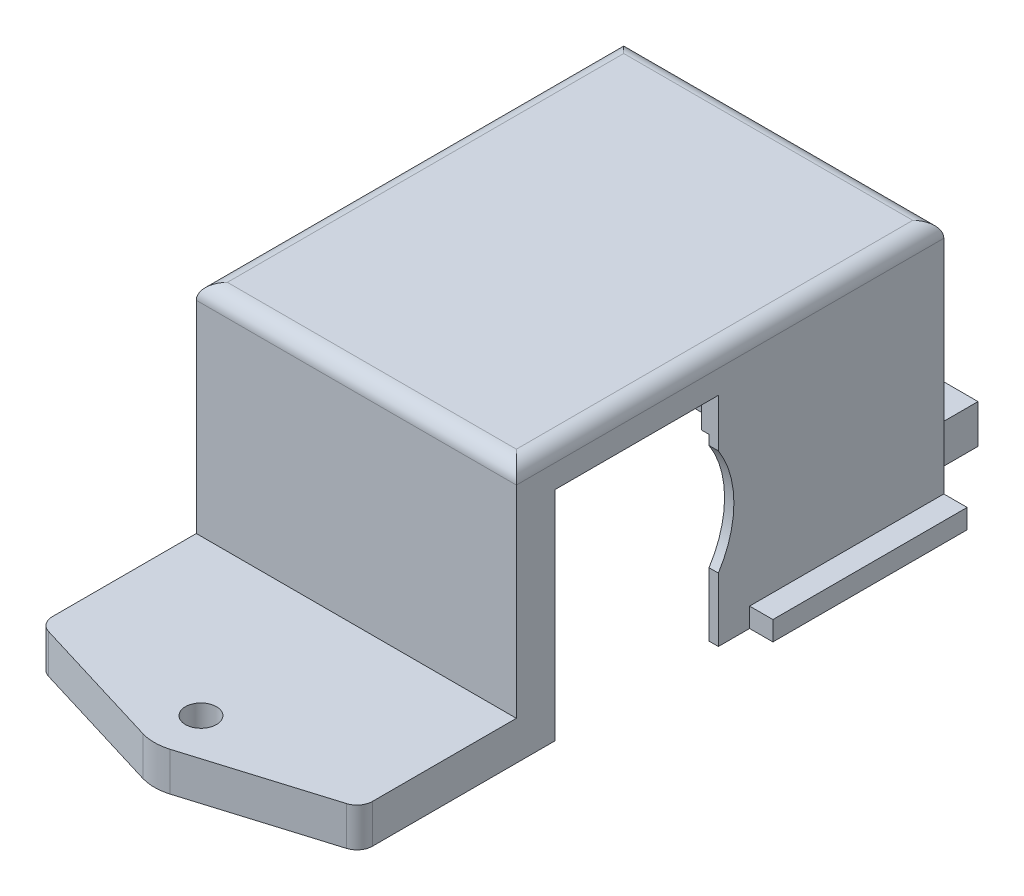
SolidWorks part; units mm, degrees
ref_plane "Front Plane" through (0, 0, 0) normal (0, 0, 1) x (1, 0, 0)
ref_plane "Top Plane" through (0, 0, 0) normal (0, 1, 0) x (1, 0, 0)
ref_plane "Right Plane" through (0, 0, 0) normal (1, 0, 0) x (0, 0, -1)
sketch "Sketch1" plane through (0, 0, 0) normal (0, 1, 0) x (1, 0, 0)
  line L1 (-19.891, 13.2956) -> (19.109, 13.2956)
  line L2 (-19.891, 13.2956) -> (-19.891, -35.9244)
  line L3 (-19.891, -35.9244) -> (19.109, -35.9244)
  line L4 (19.109, 13.2956) -> (19.109, -35.9244)
extrude "Boss-Extrude2" add sketch "Sketch1" along normal blind 30
sketch "Sketch3" plane through (0, 0, 35.9244) normal (0, 0, 1) x (1, 0, 0)
  line L0 (-19.891, 28) -> (19.109, 28)
  line L1 (-19.891, 30) -> (-19.891, 0) construction
  line L2 (19.109, 30) -> (19.109, 0) construction
  line L3 (17.109, 30) -> (17.109, 0) construction
  line L4 (-19.891, 30) -> (19.109, 30) construction
  line L5 (-19.891, 0) -> (19.109, 0) construction
  line L6 (-16.141, 30) -> (-16.141, 0)
  line L7 (-17.891, 30) -> (-17.891, 0)
  line L8 (16.109, 28) -> (16.109, -0.33)
  line L9 (-17.891, 28) -> (17.109, 28)
  line L10 (-17.891, 28) -> (-17.891, 0)
  line L11 (-17.891, 0) -> (17.109, 0)
  line L12 (17.109, 28) -> (17.109, 0)
  line L13 (-17.891, 25.5) -> (-16.141, 25.5)
  line L14 (-17.891, 25.5) -> (-17.891, 5.5)
  line L15 (-17.891, 5.5) -> (-16.141, 5.5)
  line L16 (-16.141, 25.5) -> (-16.141, 5.5)
  line L18 (16.109, 23.05) -> (17.109, 23.05)
  line L19 (16.109, 23.05) -> (16.109, 7.95)
  line L20 (16.109, 7.95) -> (17.109, 7.95)
  line L21 (17.109, 23.05) -> (17.109, 7.95)
  point P22 (-17.016, 5.5)
  point P29 (16.609, 23.05)
  point P30 (16.609, 7.95)
  line M13 (-19.891, 0) -> (19.109, 0)
  dimension "D1" = 3.75
  dimension "D2" = 2
  dimension "D3" = 1.75
  dimension "D4" = 2
  dimension "D5" = 2.5
  dimension "D6" = 5.5
  dimension "D7" = 33.25
  dimension "D8" = 1
  dimension "D9" = 4.95
  dimension "D10" = 7.95
extrude "Cut-Extrude3" cut sketch "Sketch3" against normal blind 47.22 contours L8 L0 L6 M13 | L10 L15 L6 L13 | L8 L20 L12 L18
sketch "Sketch7" plane through (-19.891, 0, 0) normal (-1, 0, 0) x (0, 0, 1)
  line L0 (8.7044, 30) -> (8.7044, 0)
  line L1 (-13.2956, 30) -> (35.9244, 30) construction
  line L2 (-13.2956, 0) -> (35.9244, 0) construction
  line L3 (-13.2956, 30) -> (-13.2956, 0) construction
  line L4 (-13.2956, 15) -> (35.9244, 15)
  line L5 (35.9244, 30) -> (35.9244, 0) construction
  circle A0 centre (24.3244, 15) radius 12.6
  dimension "D2" = 11.6
  dimension "D1" = 22
extrude "Cut-Extrude4" cut sketch "Sketch7" against normal blind 47.22 contours L2 A0 L4 | L4 A0 L2
sketch "Sketch8" plane through (-19.891, 0, 0) normal (-1, 0, 0) x (0, 0, 1)
  line L0 (-13.2956, 30) -> (35.9244, 30) construction
  line L1 (8.6339, 30) -> (35.9244, 30)
  line L2 (8.6339, 30) -> (8.6339, 0)
  line L3 (8.6339, 0) -> (35.9244, 0)
  line L4 (35.9244, 30) -> (35.9244, 0)
  line L5 (-13.2956, 0) -> (35.9244, 0) construction
  line L6 (35.9244, 10.0807) -> (35.9244, 0) construction
  line L8 (8.6339, 30) -> (17.6339, 30)
  line L9 (8.6339, 30) -> (8.6339, 27)
  line L10 (8.6339, 27) -> (17.6339, 27)
  line L11 (17.6339, 30) -> (17.6339, 27)
  line L12 (8.6339, 0) -> (17.6339, 0)
  line L13 (8.6339, 0) -> (8.6339, 4)
  line L14 (8.6339, 4) -> (17.6339, 4)
  line L15 (17.6339, 0) -> (17.6339, 4)
  line M1 (35.9244, 0) -> (35.9244, 10.0807)
  arc M2 (35.9244, 10.0807) -> (35.9244, 19.9193) centre (24.3244, 15) cw
  line M3 (35.9244, 19.9193) -> (35.9244, 30)
  line M4 (35.9244, 30) -> (-13.2956, 30)
extrude "Cut-Extrude5" cut sketch "Sketch8" against normal blind 3.75 contours L15 L3 L11 L10 L2 L14 M1 M2 M3 M4
sketch "Sketch9" plane through (19.109, 0, 0) normal (1, 0, 0) x (0, 0, -1)
  line L0 (-35.9244, 0) -> (13.2956, 0) construction
  line L1 (-35.9244, 30) -> (-13.7244, 30)
  line L2 (-35.9244, 30) -> (-35.9244, 0)
  line L3 (-35.9244, 0) -> (-13.7244, 0)
  line L4 (-13.7244, 30) -> (-13.7244, 0)
  dimension "D1" = 22.2
extrude "Cut-Extrude7" cut sketch "Sketch9" against normal through all
sketch "Sketch11" plane through (0, 0, 13.7244) normal (0, 0, 1) x (1, 0, 0)
  line L0 (-18.891, 30) -> (-18.891, 0)
  line L1 (19.109, 0) -> (-19.891, 0)
  line L2 (19.109, 0) -> (19.109, 30)
  line L3 (19.109, 30) -> (-19.891, 30)
  line L4 (-19.891, 0) -> (-19.891, 30)
  line L5 (18.309, 30) -> (18.309, 0)
  line M9 (19.109, 0) -> (19.109, 8.1882)
  line M10 (19.109, 8.1882) -> (17.109, 8.1882)
  dimension "D1" = 1
  dimension "D2" = 0.8
extrude "Cut-Extrude8" cut sketch "Sketch11" against normal through all contours L3 L5 L2 M10 | L5 L1 M10 M9
sketch "Sketch12" plane through (18.309, 0, 0) normal (1, 0, 0) x (0, 0, -1)
  line L1 (13.2956, 0) -> (-9.7044, 0)
  line L2 (13.2956, 0) -> (13.2956, 2.5)
  line L3 (13.2956, 2.5) -> (-9.7044, 2.5)
  line L4 (-9.7044, 0) -> (-9.7044, 2.5)
extrude "Boss-Extrude3" add sketch "Sketch12" along normal blind 3
sketch "Sketch13" plane through (-19.891, 0, 0) normal (-1, 0, 0) x (0, 0, 1)
  line L1 (-13.2956, 0) -> (9.7044, 0)
  line L2 (-13.2956, 0) -> (-13.2956, 2.5)
  line L3 (-13.2956, 2.5) -> (9.7044, 2.5)
  line L4 (9.7044, 0) -> (9.7044, 2.5)
extrude "Boss-Extrude4" add sketch "Sketch13" along normal blind 3
sketch "Sketch14" plane through (-16.141, 0, 0) normal (1, 0, 0) x (0, 0, -1)
  line L0 (-13.7244, 0) -> (-13.7244, 8.1882) construction
  line L1 (-13.7244, 3) -> (13.2956, 3)
  line L2 (-13.7244, 3) -> (-13.7244, 0)
  line L3 (-13.7244, 0) -> (13.2956, 0)
  line L4 (13.2956, 3) -> (13.2956, 0)
extrude "Boss-Extrude5" add sketch "Sketch14" along normal up to next
sketch "Sketch15" plane through (0, 0, 13.7244) normal (0, 0, 1) x (1, 0, 0)
  line L1 (-19.891, 0) -> (18.309, 0) construction
  line L2 (16.109, 3) -> (-16.141, 3) construction
  line L5 (-15.141, 3) -> (-15.141, 0)
  line L6 (-15.141, 0) -> (15.109, 0)
  line L7 (15.109, 0) -> (15.109, 3)
  line L8 (-15.141, 3) -> (15.109, 3)
extrude "Cut-Extrude9" cut sketch "Sketch15" against normal up to surface (25.02 mm away) up to face at (-0.141, 15.5, -11.2956)
sketch "Sketch16" plane through (0, 0, -11.2956) normal (0, 0, 1) x (1, 0, 0)
  line L1 (-15.141, 0) -> (15.109, 0)
  line L2 (-15.141, 0) -> (-15.141, 3)
  line L3 (-15.141, 3) -> (15.109, 3)
  line L4 (15.109, 0) -> (15.109, 3)
extrude "Cut-Extrude10" cut sketch "Sketch16" against normal through all
sketch "Sketch18" plane through (0, 0, -13.2956) normal (0, 0, -1) x (-1, 0, 0)
  line L0 (-15.109, 3) -> (-15.109, 15.3271)
  line L1 (15.141, 3) -> (15.141, 15.3271)
  line L2 (15.141, 15.3271) -> (-15.109, 15.3271)
  line L3 (-15.109, 15.3271) -> (-10.0511, 15.3271)
  line L4 (15.141, 15.3271) -> (10.141, 15.3271)
  line L5 (-15.0511, 17.8271) -> (-5.0511, 17.8271)
  line L6 (-15.0511, 17.8271) -> (-15.0511, 12.8271)
  line L7 (-15.0511, 12.8271) -> (-5.0511, 12.8271)
  line L8 (-5.0511, 17.8271) -> (-5.0511, 12.8271)
  line L9 (-15.0511, 17.8271) -> (-5.0511, 12.8271) construction
  line L10 (-15.0511, 12.8271) -> (-5.0511, 17.8271) construction
  line L12 (5.141, 17.8271) -> (15.141, 17.8271)
  line L13 (5.141, 17.8271) -> (5.141, 12.8271)
  line L14 (5.141, 12.8271) -> (15.141, 12.8271)
  line L15 (15.141, 17.8271) -> (15.141, 12.8271)
  line L16 (5.141, 17.8271) -> (15.141, 12.8271) construction
  line L17 (5.141, 12.8271) -> (15.141, 17.8271) construction
sketch "Sketch23" plane through (-19.891, 0, 0) normal (-1, 0, 0) x (0, 0, 1)
  line L0 (-13.2956, 2.5) -> (-13.2956, 30)
  line L1 (-13.2956, 30) -> (13.7244, 30)
  line L2 (13.7244, 30) -> (13.7244, 27)
  line L3 (13.7244, 27) -> (8.6339, 27)
  line L4 (8.6339, 27) -> (8.6339, 4)
  line L5 (8.6339, 4) -> (13.7244, 4)
  line L6 (13.7244, 4) -> (13.7244, 0)
  line L7 (13.7244, 0) -> (9.7044, 0)
  line L8 (9.7044, 0) -> (9.7044, 2.5)
  line L9 (9.7044, 2.5) -> (-13.2956, 2.5)
sketch "Sketch24" plane through (-22.891, 0, 0) normal (-1, 0, 0) x (0, 0, 1)
  line L0 (-13.2956, 2.5) -> (9.7044, 2.5)
  line L1 (9.7044, 2.5) -> (9.7044, 0)
  line L2 (9.7044, 0) -> (-13.2956, 0)
  line L3 (-13.2956, 0) -> (-13.2956, 2.5)
extrude "Boss-Extrude8" add sketch "Sketch24" along normal blind 6
sketch "Sketch25" plane through (-19.891, 0, 0) normal (-1, 0, 0) x (0, 0, 1)
  line L0 (-13.2956, 30) -> (13.7244, 30)
  line L1 (13.7244, 30) -> (13.7244, 27)
  line L2 (13.7244, 27) -> (8.6339, 27)
  line L3 (8.6339, 27) -> (8.6339, 4)
  line L4 (8.6339, 4) -> (13.7244, 4)
  line L5 (13.7244, 4) -> (13.7244, 0)
  line L6 (13.7244, 0) -> (9.7044, 0)
  line L7 (9.7044, 0) -> (9.7044, 2.5)
  line L8 (9.7044, 2.5) -> (-13.2956, 2.5)
  line L9 (-13.2956, 2.5) -> (-13.2956, 30)
extrude "Boss-Extrude9" add sketch "Sketch25" along normal blind 3
sketch "Sketch26" plane through (0, 30, 0) normal (0, 1, 0) x (1, 0, 0)
  line L1 (-22.891, 13.2956) -> (18.309, 13.2956)
  line L2 (-22.891, 13.2956) -> (-22.891, -13.7244)
  line L3 (-22.891, -13.7244) -> (18.309, -13.7244)
  line L4 (18.309, 13.2956) -> (18.309, -13.7244)
extrude "Boss-Extrude10" add sketch "Sketch26" along normal blind 3
sketch "Sketch29" plane through (0, 25.5, 0) normal (0, -1, 0) x (1, 0, 0)
  line L1 (-17.891, -11.2956) -> (-13.6266, -11.2956)
  line L2 (-17.891, -11.2956) -> (-17.891, 15.1522)
  line L3 (-17.891, 15.1522) -> (-13.6266, 15.1522)
  line L4 (-13.6266, -11.2956) -> (-13.6266, 15.1522)
extrude "Cut-Extrude14" cut sketch "Sketch29" along normal through all
sketch "Sketch30" plane through (0, 23.05, 0) normal (0, -1, 0) x (-1, 0, 0)
  line L1 (-17.109, 11.2956) -> (-13.1276, 11.2956)
  line L2 (-17.109, 11.2956) -> (-17.109, -22.36)
  line L3 (-17.109, -22.36) -> (-13.1276, -22.36)
  line L4 (-13.1276, 11.2956) -> (-13.1276, -22.36)
extrude "Cut-Extrude15" cut sketch "Sketch30" along normal through all
sketch "Sketch34" plane through (0, 0, -13.2956) normal (0, 0, -1) x (-1, 0, 0)
  line L0 (-18.309, 33) -> (-18.309, 2.5)
  line L1 (-18.309, 2.5) -> (-21.309, 2.5)
  line L2 (-21.309, 2.5) -> (-21.309, 0)
  line L3 (-21.309, 0) -> (28.891, 0)
  line L4 (28.891, 0) -> (28.891, 2.5)
  line L5 (28.891, 2.5) -> (22.891, 2.5)
  line L6 (22.891, 2.5) -> (22.891, 33)
  line L7 (22.891, 33) -> (-18.309, 33)
extrude "Boss-Extrude15" add sketch "Sketch34" against normal up to surface (2 mm away) up to face at (-0.141, 13.2583, -11.2956)
sketch "Sketch35" plane through (0, 0, -13.2956) normal (0, 0, -1) x (-1, 0, 0)
  line L0 (-18.309, 33) -> (-18.309, 2.5)
  line L1 (-18.309, 2.5) -> (-21.309, 2.5)
  line L2 (-21.309, 2.5) -> (-21.309, 0)
  line L3 (-21.309, 0) -> (-21.309, 2.5) construction
  line L4 (-21.309, 0) -> (28.891, 0)
  line L5 (28.891, 0) -> (28.891, 2.5)
  line L6 (28.891, 2.5) -> (22.891, 2.5)
  line L7 (22.891, 2.5) -> (22.891, 33)
  line L8 (22.891, 33) -> (-18.309, 33)
extrude "Boss-Extrude16" add sketch "Sketch35" along normal blind 2
sketch "Sketch36" plane through (0, 0, 13.7244) normal (0, 0, 1) x (1, 0, 0)
  line L0 (18.309, 33) -> (18.309, 21.8118) construction
  line L1 (-22.891, 33) -> (18.309, 33)
  line L2 (-22.891, 33) -> (-22.891, 28.0065)
  line L3 (-22.891, 28.0065) -> (18.309, 28.0065)
  line L4 (18.309, 33) -> (18.309, 28.0065)
extrude "Boss-Extrude17" add sketch "Sketch36" along normal blind 26
sketch "Sketch37" plane through (0, 28.0065, 0) normal (0, -1, 0) x (-1, 0, 0)
  line L0 (-18.309, -39.7244) -> (-18.309, -13.7244) construction
  line L1 (22.891, -39.7244) -> (-18.309, -39.7244)
  line L2 (22.891, -39.7244) -> (22.891, -34.7244)
  line L3 (22.891, -34.7244) -> (-18.309, -34.7244)
  line L4 (-18.309, -39.7244) -> (-18.309, -34.7244)
extrude "Boss-Extrude18" add sketch "Sketch37" along normal up to surface (28.0065 mm away) up to face at (-2.1577, 0, 3.3777)
sketch "Sketch38" plane through (0, 0, 39.7244) normal (0, 0, 1) x (1, 0, 0)
  line L0 (18.309, 0) -> (18.309, 33) construction
  line L1 (-22.891, 0) -> (18.309, 0)
  line L2 (-22.891, 0) -> (-22.891, 5)
  line L3 (-22.891, 5) -> (18.309, 5)
  line L4 (18.309, 0) -> (18.309, 5)
extrude "Boss-Extrude19" add sketch "Sketch38" along normal blind 20
sketch "Sketch39" plane through (0, 5, 0) normal (0, 1, 0) x (1, 0, 0)
  line L0 (18.309, -59.7244) -> (-22.891, -59.7244) construction
  line L1 (-22.891, -59.7244) -> (-4.0386, -65.4643)
  line L2 (18.309, -59.7244) -> (-0.5435, -65.4643)
  line L3 (-22.891, -59.7244) -> (-8.291, -59.7244)
  line L4 (-8.291, -59.7244) -> (18.309, -59.7244)
  circle A0 centre (-2.291, -59.7244) radius 6
  circle A1 centre (-2.291, -59.7244) radius 2
  line M6 (-22.891, -59.7244) -> (18.309, -59.7244)
extrude "Boss-Extrude21" add sketch "Sketch39" against normal up to surface (5 mm away) contours A0 L1 M6 | A1 A0 M6 | A0 L2 L4 up to face at (-2.291, 0, 47.2244)
sketch "Sketch40" plane through (0, 5, 0) normal (0, 1, 0) x (1, 0, 0)
  line L0 (-0.291, -59.7244) -> (-4.291, -59.7244) construction
  circle A0 centre (-2.291, -59.7244) radius 2
extrude "Cut-Extrude16" cut sketch "Sketch40" against normal through all
fillet "Fillet1" radius 2 6 edges at (18.309, 33, 12.2144) (-2.291, 33, -15.2956) (-22.891, 33, 12.2144) (-2.291, 33, 39.7244) (-22.891, 2.5, 59.7244) (18.309, 2.5, 59.7244)
sketch "Sketch41" plane through (0, 0, -15.2956) normal (0, 0, -1) x (-1, 0, 0)
  line L1 (2.291, 5) -> (17.291, 5)
  line L2 (17.291, 5) -> (17.291, 0)
  line L3 (2.291, 5) -> (-12.709, 5)
  line L5 (-12.709, 5) -> (-12.709, 0)
  line L6 (-21.309, 0) -> (28.891, 0) construction
  line L7 (-12.709, 0) -> (2.291, 0)
  line L9 (2.291, 0) -> (17.291, 0)
  line L10 (-12.709, 0) -> (2.291, 0)
  line M6 (-21.309, 0) -> (28.891, 0)
extrude "Boss-Extrude22" add sketch "Sketch41" along normal blind 10 contours L3 L5 L2 L1 M6
